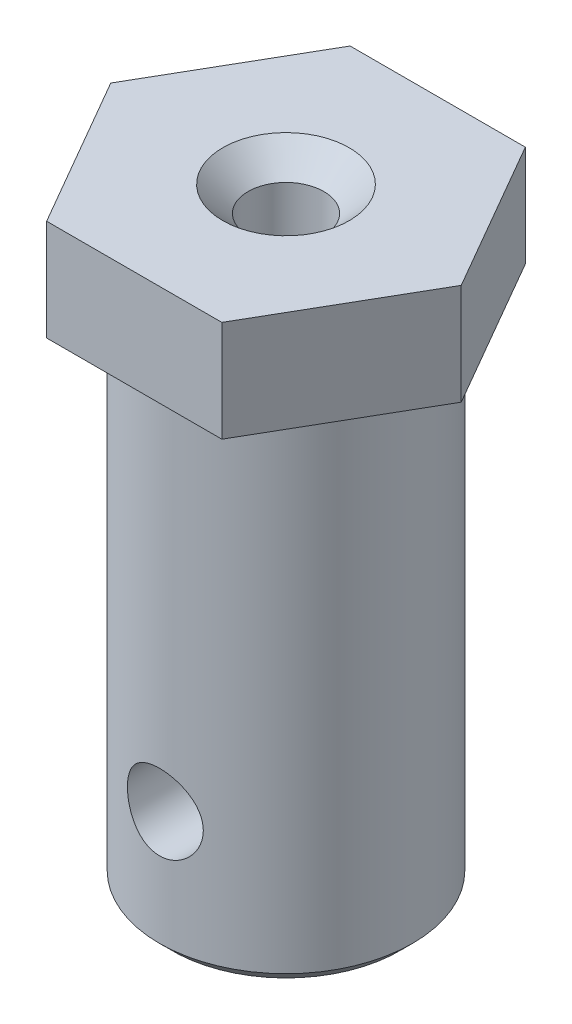
SolidWorks part; units mm, degrees
ref_plane "Ön Düzlem" through (0, 0, 0) normal (0, 0, 1) x (1, 0, 0)
ref_plane "Üst Düzlem" through (0, 0, 0) normal (0, 1, 0) x (1, 0, 0)
ref_plane "Sağ Düzlem" through (0, 0, 0) normal (1, 0, 0) x (0, 0, -1)
sketch "Çizim1" plane through (0, 0, 0) normal (0, 1, 0) x (1, 0, 0)
  line L1 (6.9282, 0) -> (3.4641, 6)
  line L2 (3.4641, 6) -> (-3.4641, 6)
  line L3 (-3.4641, 6) -> (-6.9282, 0)
  line L4 (-6.9282, 0) -> (-3.4641, -6)
  line L5 (-3.4641, -6) -> (3.4641, -6)
  line L6 (3.4641, -6) -> (6.9282, 0)
  circle A0 centre (0, 0) radius 6 construction
  dimension "D1" = 12
extrude "Yükseklik-Ekstrüzyon1" add sketch "Çizim1" along normal blind 4
sketch "Çizim2" plane through (0, 0, 0) normal (0, -1, 0) x (1, 0, 0)
  circle A0 centre (0, 0) radius 5
  dimension "D1" = 10
extrude "Yükseklik-Ekstrüzyon2" add sketch "Çizim2" along normal blind 20
fillet "Radyus3" radius 0.5 1 edges at (0, 0, -5)
chamfer "Pah7" distance 0.5 angle 45 1 edges at (0, -20, -5)
sketch "Çizim3" plane through (0, 4, 0) normal (0, 1, 0) x (1, 0, 0)
  circle A0 centre (0, 0) radius 1.5
  dimension "D1" = 3
sketch "Çizim4" plane through (0, -20, 0) normal (0, -1, 0) x (1, 0, 0)
  circle A0 centre (0, 0) radius 2.5
  dimension "D1" = 5
extrude "Kes-Ekstrüzyon3" cut sketch "Çizim4" against normal blind 15
extrude "Kes-Ekstrüzyon4" cut sketch "Çizim3" against normal blind 10 contours A0
ref_plane "Düzlem1" through (0, 0, 6) normal (0, 0, 1) x (1, 0, 0)
sketch "Çizim8" plane through (0, 0, 6) normal (0, 0, 1) x (1, 0, 0)
  line L0 (0, 4) -> (0, -21.57) construction
  line L1 (-3.4641, 4) -> (3.4641, 4) construction
  line L2 (-4.5, -20) -> (4.5, -20) construction
  circle A0 centre (0, -15) radius 1.5
  dimension "D1" = 3
  dimension "D2" = 5
extrude "Kes-Ekstrüzyon5" cut sketch "Çizim8" against normal blind 6 contours A0
chamfer "Pah8" distance 1 1 edges at (0, -20, -2.5)
chamfer "Pah9" distance 1 angle 45 1 edges at (0, 4, 1.5)
